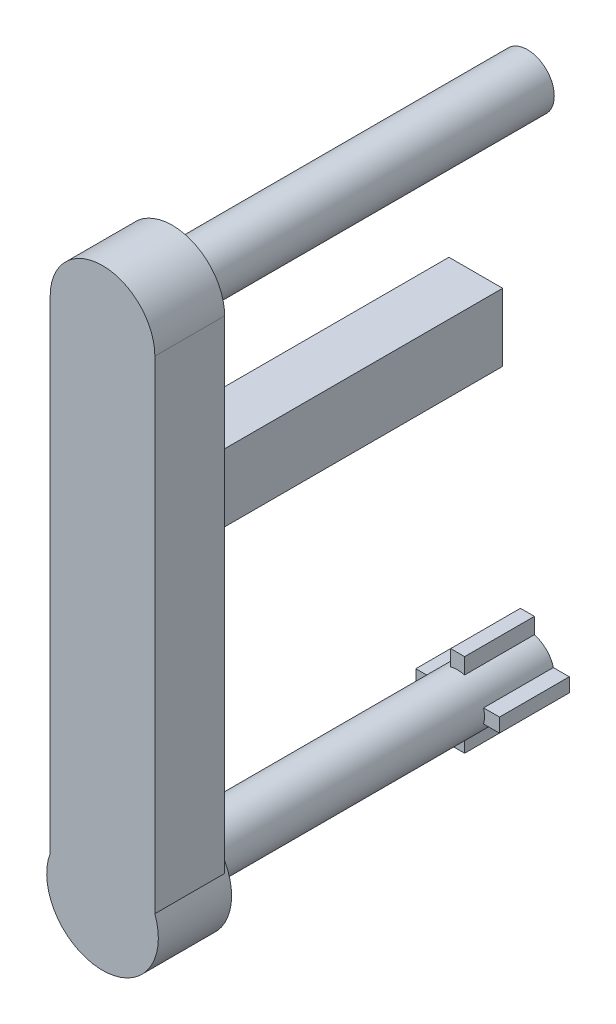
SolidWorks part; units mm, degrees
ref_plane "Piano frontale" through (0, 0, 0) normal (0, 0, 1) x (1, 0, 0)
ref_plane "Piano superiore" through (0, 0, 0) normal (0, 1, 0) x (1, 0, 0)
ref_plane "Piano destro" through (0, 0, 0) normal (1, 0, 0) x (0, 0, -1)
other "Graphic1"
other "Graphic (Closed) -1"
sketch "Sketch1" plane through (0, 0, 0) normal (0, 0, 1) x (1, 0, 0)
  circle A0 centre (0, 0) radius 20.1563
  circle A1 centre (0, 0) radius 8
  dimension "D1" = 16
extrude "Boss-Extrude1" add sketch "Sketch1" against normal blind 10.5 contours A1
sketch "Sketch2" plane through (0, 0, -10.5) normal (0, 0, -1) x (-1, 0, 0)
  circle A0 centre (0, 0) radius 3.85
  dimension "D1" = 7.7
extrude "Boss-Extrude2" add sketch "Sketch2" along normal blind 60
sketch "Sketch3" plane through (0, 0, -70.5) normal (0, 0, -1) x (-1, 0, 0)
  line L0 (-6, 1) -> (-1, 1)
  line L1 (-1, 6) -> (1, 6)
  line L4 (0, 6) -> (0, 0) construction
  line L5 (6, 1) -> (6, -1)
  line L6 (1, -6) -> (-1, -6)
  line L7 (-6, -1) -> (-6, 1)
  line L8 (-1, 1) -> (-1, 6)
  line L9 (1, 6) -> (1, 1)
  line L10 (1, 1) -> (6, 1)
  line L11 (6, -1) -> (1, -1)
  line L12 (1, -1) -> (1, -6)
  line L13 (-1, -6) -> (-1, -1)
  line L14 (-1, -1) -> (-6, -1)
  point P16 (0, 0)
  dimension "D1" = 1
  dimension "D2" = 6
  dimension "D3" = 4
extrude "Boss-Extrude3" add sketch "Sketch3" against normal blind 10 from offset 9.6 offset against normal yes
sketch "Sketch6" plane through (0, 0, -70.5) normal (0, 0, -1) x (-1, 0, 0)
  circle A1 centre (0, 0) radius 3.85
  circle A2 centre (0, 0) radius 3.85
  dimension "D1" = 0
extrude "Cut-Extrude1" cut sketch "Sketch6" against normal up to surface (9.6 mm away) up to face at (4.892, 0, -60.9)
sketch "Sketch7" plane through (0, 0, 0) normal (0, 0, 1) x (1, 0, 0)
  line L0 (0, 0) -> (0, 72) construction
  line L1 (-7.5, 72) -> (-7.5, 2.7839)
  line L2 (7.5, 72) -> (7.5, 2.7839)
  line L3 (7.5, 2.7839) -> (-7.5, 2.7839)
  arc A0 (7.5, 72) -> (-7.5, 72) centre (0, 72) ccw
  circle A2 centre (0, 0) radius 8 construction
  dimension "D2" = 7.5
  dimension "D1" = 72
  dimension "D3" = 15
extrude "Boss-Extrude4" add sketch "Sketch7" against normal blind 10
sketch "Sketch8" plane through (0, 0, -10) normal (0, 0, -1) x (-1, 0, 0)
  circle A0 centre (0, 72) radius 4.5
  dimension "D1" = 9
extrude "Boss-Extrude5" add sketch "Sketch8" along normal blind 0.5
sketch "Sketch9" plane through (0, 0, -10.5) normal (0, 0, -1) x (-1, 0, 0)
  circle A0 centre (0, 72) radius 3.85
  dimension "D1" = 7.7
extrude "Boss-Extrude6" add sketch "Sketch9" along normal up to surface (50.4 mm away) up to face at (0, 0, -60.9)
sketch "Sketch10" plane through (0, 0, 0) normal (0, 0, 1) x (1, 0, 0)
  circle A0 centre (0, 0) radius 22.5
  point P4 (-80.9181, -216.2945)
  dimension "D1" = 45
sketch "Sketch11" plane through (0, 0, -10) normal (0, 0, -1) x (-1, 0, 0)
  line L0 (-4, 42) -> (-4, 52) construction
  line L1 (-4, 52) -> (3.9994, 52) construction
  line L2 (3.9994, 52) -> (3.9994, 42) construction
  line L3 (3.9994, 42) -> (-4, 42) construction
  line L4 (-4, 42) -> (-4, 52) construction
  line L5 (-4, 52) -> (3.9994, 52) construction
  line L6 (3.9994, 52) -> (3.9994, 42) construction
  line L7 (3.9994, 42) -> (-4, 42) construction
  line L8 (-3.85, 42.15) -> (-3.85, 51.85)
  line L9 (-3.85, 51.85) -> (3.8494, 51.85)
  line L10 (3.8494, 51.85) -> (3.8494, 42.15)
  line L11 (3.8494, 42.15) -> (-3.85, 42.15)
  dimension "D1" = 0.15
extrude "Boss-Extrude7" add sketch "Sketch11" along normal up to surface (43.5 mm away)
sketch "Sketch12" plane through (0, 0, -53.5) normal (0, 0, -1) x (-1, 0, 0)
  circle A0 centre (-0.0003, 47) radius 1.75 construction
  circle A1 centre (-0.0003, 47) radius 1.75
extrude "Cut-Extrude2" cut sketch "Sketch12" against normal blind 10
